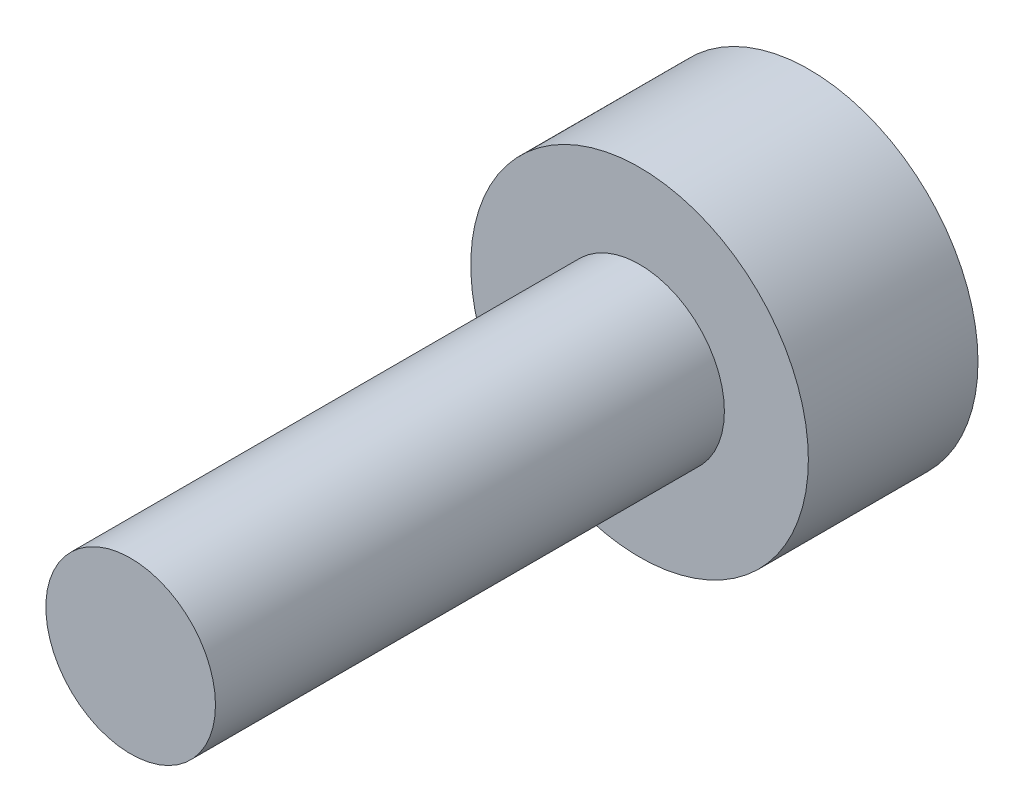
SolidWorks part; units mm, degrees
material "AISI 304"
ref_plane "前视基准面" through (0, 0, 0) normal (0, 0, 1) x (1, 0, 0)
ref_plane "上视基准面" through (0, 0, 0) normal (0, 1, 0) x (1, 0, 0)
ref_plane "右视基准面" through (0, 0, 0) normal (1, 0, 0) x (0, 0, -1)
sketch "草图1" plane through (0, 0, 0) normal (0, 0, 1) x (1, 0, 0)
  circle A0 centre (0, 0) radius 1.99
  dimension "D1" = 3.98
extrude "凸台-拉伸1" add sketch "草图1" along normal blind 2
sketch "草图2" plane through (0, 0, 2) normal (0, 0, 1) x (1, 0, 0)
  circle A0 centre (0, 0) radius 1
  dimension "D1" = 2
extrude "凸台-拉伸2" add sketch "草图2" along normal blind 6
cosmetic thread "装饰螺纹线1" parameters "D2"=1.567
sketch "草图3" plane through (0, 0, 0) normal (0, 0, -1) x (-1, 0, 0)
  line L1 (0.9007, 0) -> (0.4503, 0.78)
  line L2 (0.4503, 0.78) -> (-0.4503, 0.78)
  line L3 (-0.4503, 0.78) -> (-0.9007, 0)
  line L4 (-0.9007, 0) -> (-0.4503, -0.78)
  line L5 (-0.4503, -0.78) -> (0.4503, -0.78)
  line L6 (0.4503, -0.78) -> (0.9007, 0)
  circle A0 centre (0, 0) radius 0.78 construction
  dimension "D1" = 1.56
extrude "切除-拉伸1" cut sketch "草图3" against normal blind 1
